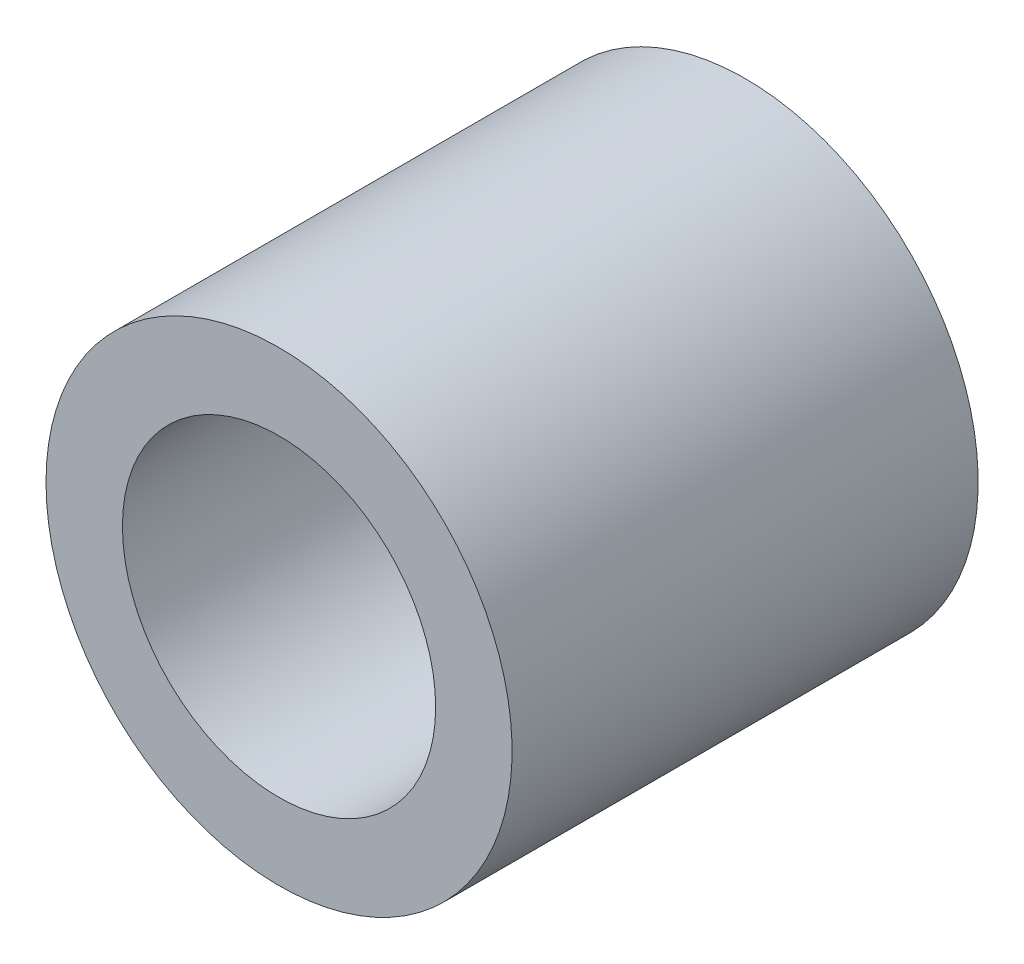
SolidWorks part; units mm, degrees
ref_plane "Front Plane" through (0, 0, 0) normal (0, 0, 1) x (1, 0, 0)
ref_plane "Top Plane" through (0, 0, 0) normal (0, 1, 0) x (1, 0, 0)
ref_plane "Right Plane" through (0, 0, 0) normal (1, 0, 0) x (0, 0, -1)
sketch "Sketch1" plane through (0, 0, 0) normal (0, 0, 1) x (1, 0, 0)
  circle A0 centre (0, 0) radius 4.7625
  circle A1 centre (0, 0) radius 3.2004
  dimension "D1" = 9.525
  dimension "ID" = 6.4008
extrude "Extrude1" add sketch "Sketch1" along normal mid plane 9.525
sketch "Sketch2" plane through (0, 0, 0) normal (1, 0, 0) x (0, 0, -1)
  line L0 (-4.7625, -3.2004) -> (4.7625, -3.2004) construction
  line L3 (4.7625, 3.2004) -> (-4.7625, 3.2004) construction
  line L5 (-4.7625, -3.2004) -> (4.7625, -3.2004)
  line L6 (4.7625, 3.2004) -> (-4.7625, 3.2004)
sketch "Sketch4" plane through (0, 0, 4.7625) normal (0, 0, 1) x (1, 0, 0)
  line L0 (0, 0) -> (-2.263, 2.263)
  line L1 (0, -17.4625) -> (0, 17.4625) construction
  circle A0 centre (0, 0) radius 3.2004 construction
  dimension "D1" = 45
